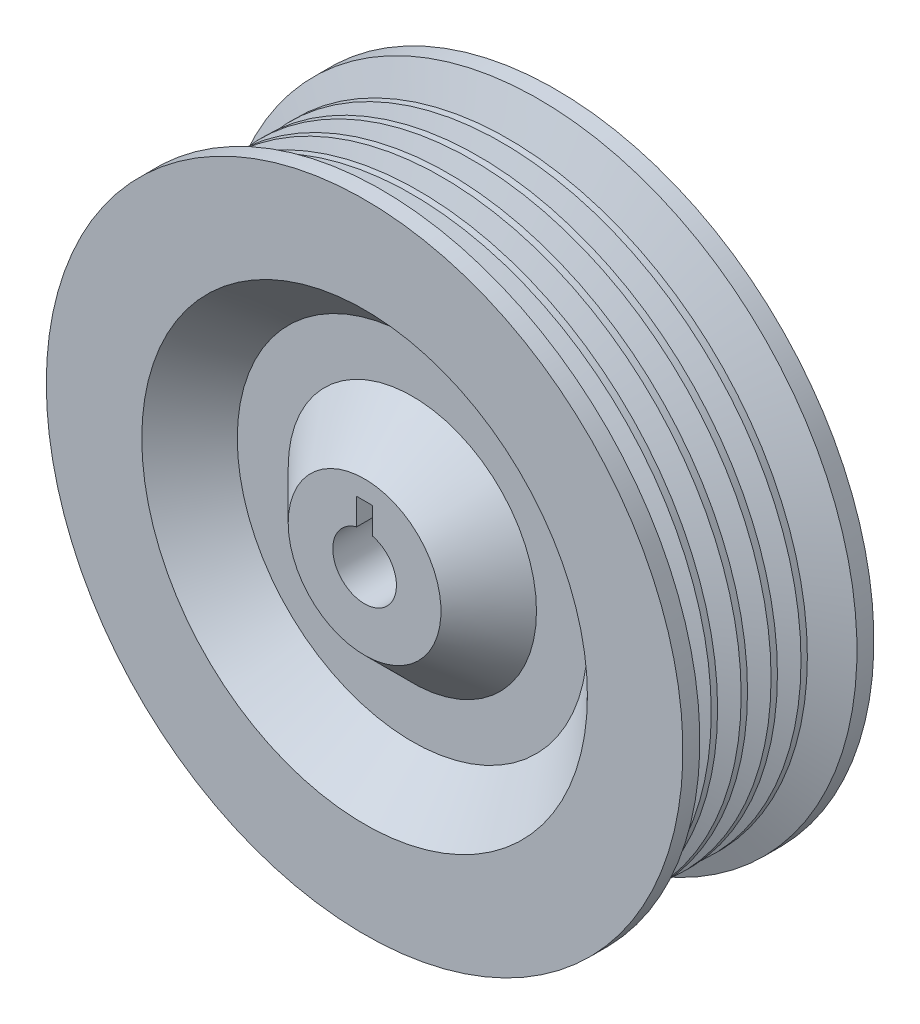
SolidWorks part; units mm, degrees
ref_plane "Спереди" through (0, 0, 0) normal (0, 0, 1) x (1, 0, 0)
ref_plane "Сверху" through (0, 0, 0) normal (0, 1, 0) x (1, 0, 0)
ref_plane "Справа" through (0, 0, 0) normal (1, 0, 0) x (0, 0, -1)
sketch "Эскиз1" plane through (0, 0, 0) normal (1, 0, 0) x (0, 0, -1)
  line L0 (0, 0) -> (0, 12)
  line L1 (0, 12) -> (7.5, 19.5)
  line L2 (7.5, 19.5) -> (7.5, 27.5)
  line L3 (7.5, 27.5) -> (0, 35)
  line L4 (0, 35) -> (0, 50)
  line L5 (0, 50) -> (2.6581, 50)
  line L6 (2.6581, 50) -> (5.2993, 42.7433)
  line L7 (5.9007, 42.7433) -> (7.45, 47)
  line L8 (8.45, 47) -> (9.9993, 42.7433)
  line L9 (10.6007, 42.7433) -> (12.15, 47)
  line L10 (30, 50) -> (30, 35)
  line L11 (30, 35) -> (22.5, 27.5)
  line L12 (22.5, 27.5) -> (22.5, 19.5)
  line L13 (22.5, 19.5) -> (30, 12)
  line L14 (30, 12) -> (30, 0)
  line L15 (30, 0) -> (0, 0)
  line L16 (13.15, 47) -> (14.6993, 42.7433)
  line L17 (15.3007, 42.7433) -> (16.85, 47)
  line L18 (17.85, 47) -> (19.3993, 42.7433)
  line L19 (20.0007, 42.7433) -> (21.55, 47)
  line L20 (22.55, 47) -> (24.0993, 42.7433)
  line L21 (24.7007, 42.7433) -> (27.3419, 50)
  line L22 (27.3419, 50) -> (30, 50)
  line L23 (7.45, 47) -> (8.45, 47)
  line L25 (15, 42.8528) -> (15, 50) construction
  line L26 (0, 50) -> (30, 50) construction
  line L27 (12.15, 47) -> (13.15, 47)
  line L28 (16.85, 47) -> (17.85, 47)
  line L29 (21.55, 47) -> (22.55, 47)
  arc A0 (5.9007, 42.7433) -> (5.2993, 42.7433) centre (5.6, 42.8528) cw
  arc A5 (24.7007, 42.7433) -> (24.0993, 42.7433) centre (24.4, 42.8528) cw
  arc A6 (20.0007, 42.7433) -> (19.3993, 42.7433) centre (19.7, 42.8528) cw
  arc A7 (15.3007, 42.7433) -> (14.6993, 42.7433) centre (15, 42.8528) cw
  arc A8 (10.6007, 42.7433) -> (9.9993, 42.7433) centre (10.3, 42.8528) cw
  point P7 (0, 0)
  point P9 (5.6, 42.5328)
  point P11 (0, 0)
  point P12 (5.9007, 42.2715)
  dimension "D2" = 3
  dimension "D3" = 0.32
  dimension "D5" = 4.7
  dimension "D6" = 1
  dimension "D4" = 50
  dimension "D7" = 30
  dimension "D8" = 12
  dimension "D11" = 20
  dimension "D12" = 15
  dimension "D13" = 40
  dimension "D18" = 15
revolve "Повернуть1" add sketch "Эскиз1" angle 360 about L15
sketch "Эскиз2" plane through (0, 0, -30) normal (0, 0, -1) x (-1, 0, 0)
  line L0 (-1.25, 4.8412) -> (-1.25, 9)
  line L1 (-1.25, 9) -> (1.25, 9)
  line L2 (1.25, 9) -> (1.25, 4.8412)
  line L3 (0, 9) -> (0, 0) construction
  circle A1 centre (0, 0) radius 5
  point P7 (0, -5)
  dimension "D1" = 10
  dimension "D2" = 2.5
  dimension "D3" = 14
extrude "Вырез-Вытянуть1" cut sketch "Эскиз2" against normal through all
